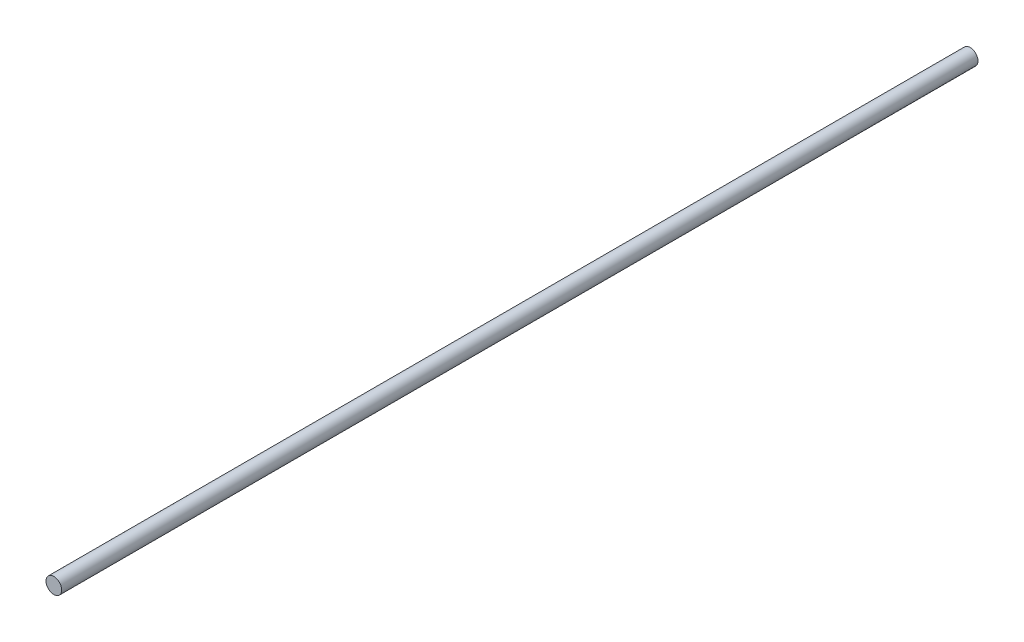
SolidWorks part; units mm, degrees
material "AISI 304"
ref_plane "Спереди" through (0, 0, 0) normal (0, 0, 1) x (1, 0, 0)
ref_plane "Сверху" through (0, 0, 0) normal (0, 1, 0) x (1, 0, 0)
ref_plane "Справа" through (0, 0, 0) normal (1, 0, 0) x (0, 0, -1)
sketch "Sketch1" plane through (0, 0, 0) normal (0, 0, 1) x (1, 0, 0)
  circle A0 centre (0, 0) radius 3
  dimension "D1" = 6
extrude "Boss-Extrude1" add sketch "Sketch1" along normal blind 350
